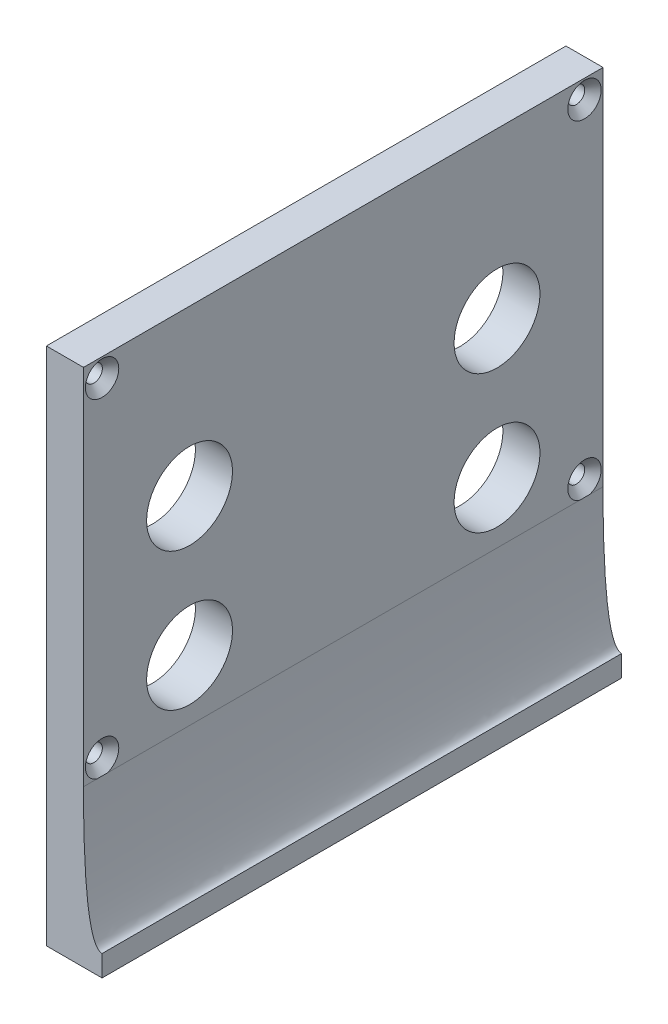
SolidWorks part; units mm, degrees
ref_plane "Front Plane" through (0, 0, 0) normal (0, 0, 1) x (1, 0, 0)
ref_plane "Top Plane" through (0, 0, 0) normal (0, 1, 0) x (1, 0, 0)
ref_plane "Right Plane" through (0, 0, 0) normal (1, 0, 0) x (0, 0, -1)
sketch "Sketch1" plane through (0, 0, 0) normal (0, 0, 1) x (1, 0, 0)
  line L0 (-46.8387, 41.5675) -> (-46.8387, -56.4325)
  line L1 (-46.8387, -56.4325) -> (-36.3387, -56.4325)
  line L2 (-36.3387, -56.4325) -> (-36.3387, -52.4325)
  line L3 (-46.8387, 41.5675) -> (-39.8387, 41.5675)
  line L4 (-39.8387, 41.5675) -> (-39.8387, -26.9325)
  line L5 (-39.8387, -26.9325) -> (-39.8387, -52.4325) construction
  line L6 (-39.8387, -52.4325) -> (-36.3387, -52.4325) construction
  spline S0 degree 2 poles (-39.8387, -26.9325) (-39.8387, -52.4325) (-36.3387, -52.4325) knots 0 0 0 1 1 1
extrude "Boss-Extrude1" add sketch "Sketch1" along normal blind 98
sketch "Sketch2" plane through (-46.8387, 0, 0) normal (-1, 0, 0) x (0, 0, 1)
  line L0 (0, 41.5675) -> (20, 41.5675) construction
  line L1 (98, 41.5675) -> (0, 41.5675) construction
  line L2 (20, 41.5675) -> (20, 10.5675) construction
  line L3 (20, 10.5675) -> (20, -15.4325) construction
  line L4 (98, 41.5675) -> (78, 41.5675) construction
  line L5 (78, 41.5675) -> (78, 10.5675) construction
  line L6 (78, 10.5675) -> (78, -15.4325) construction
  circle A0 centre (20, 10.5675) radius 8.1
  circle A1 centre (78, 10.5675) radius 8.1
  circle A2 centre (78, -15.4325) radius 8.1
  circle A3 centre (20, -15.4325) radius 8.1
  dimension "D1" = 20
  dimension "D2" = 31
  dimension "D3" = 26
  dimension "D4" = 20
  dimension "D5" = 31
  dimension "D6" = 26
extrude "Cut-Extrude1" cut sketch "Sketch2" against normal through all contours A0 | A2 | A1 | A3
sketch "Sketch6" plane through (-39.8387, 0, 0) normal (1, 0, 0) x (0, 0, -1)
  line L0 (-98, 41.5675) -> (-94.5, 41.5675) construction
  line L1 (-98, 41.5675) -> (0, 41.5675) construction
  line L2 (-94.5, 41.5675) -> (-94.5, 38.0675) construction
  line L3 (-94.5, 38.0675) -> (-94.5, -23.9325) construction
  line L4 (-94.5, -23.9325) -> (-3.5, -23.9325) construction
  line L5 (-3.5, -23.9325) -> (-3.5, 38.0675) construction
hole_wizard "CSK for M3 Flat Head Machine Screw2" positions "Sketch7" profile "Sketch8" countersink size "M3" standard "ANSI Metric"
sketch "Sketch7" plane through (-39.8387, 0, 0) normal (1, 0, 0) x (0, 0, -1)
  point P0 (-94.5, 38.0675)
  point P3 (-94.5, -23.9325)
  point P6 (-3.5, -23.9325)
  point P9 (-3.5, 38.0675)
sketch "Sketch8" plane through (-39.8387, 38.0675, 94.5) normal (0, 1, 0) x (0, 0, -1)
  line L0 (0, 0) -> (0, 10.9614)
  line L1 (0, 10.9614) -> (1.6, 10)
  line L2 (1.6, 10) -> (1.6, 1.55)
  line L3 (1.6, 1.55) -> (3.15, 0)
  line L5 (3.15, 0) -> (0, 0)
  line L6 (-1.6, 1.55) -> (-3.15, 0) construction
  line L10 (0, 10.9614) -> (-1.6, 10) construction
  line L11 (0, -6.35) -> (0, 107.95) construction
  dimension "Hole Dia." = 3.2
  dimension "Hole Depth" = 10
  dimension "Near C'Sink Dia." = 6.3
  dimension "Near C'Sink Angle" = 90
  dimension "Drill Angle" = 118
sketch "Sketch9" plane through (-46.8387, 0, 0) normal (-1, 0, 0) x (0, 0, 1)
  line L0 (49, 41.5675) -> (39.5, 41.5675) construction
  line L1 (39.5, 41.5675) -> (39.5, 40.0675) construction
  line L3 (39.5, 40.0675) -> (69, 40.0675)
  line L4 (39.5, 40.0675) -> (39.5, 33.0675)
  line L5 (39.5, 33.0675) -> (69, 33.0675)
  line L6 (69, 40.0675) -> (69, 33.0675)
extrude "Cut-Extrude2" cut sketch "Sketch9" against normal blind 2.5
